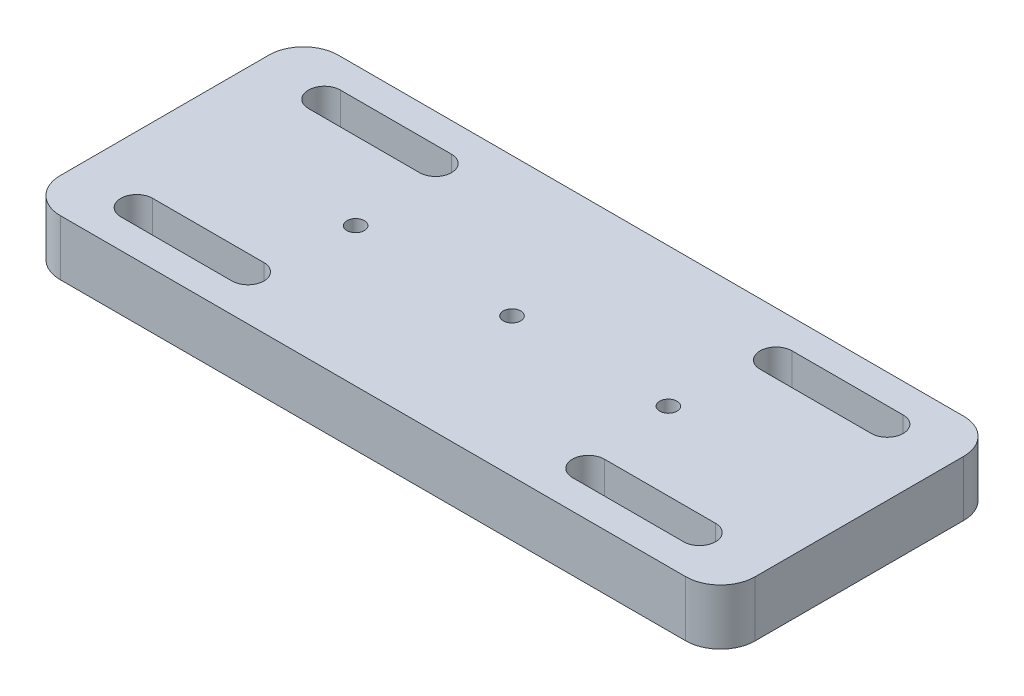
SolidWorks part; units mm, degrees
material "6061 合金"
ref_plane "前视基准面" through (0, 0, 0) normal (0, 0, 1) x (1, 0, 0)
ref_plane "上视基准面" through (0, 0, 0) normal (0, 1, 0) x (1, 0, 0)
ref_plane "右视基准面" through (0, 0, 0) normal (1, 0, 0) x (0, 0, -1)
sketch "草图1" plane through (0, 0, 0) normal (0, 1, 0) x (1, 0, 0)
  line L0 (-40.5, 13.5) -> (-24.5, 13.5) construction
  line L1 (-50, -20) -> (50, -20)
  line L2 (-50, -20) -> (-50, 20)
  line L3 (-50, 20) -> (50, 20)
  line L4 (50, -20) -> (50, 20)
  line L5 (0, 20) -> (0, -20) construction
  line L6 (-50, 0) -> (50, 0) construction
  line L7 (-30, -4) -> (30, -4) construction
  line L8 (-30, -4) -> (-30, 4) construction
  line L9 (-30, 4) -> (30, 4) construction
  line L10 (30, -4) -> (30, 4) construction
  line L11 (0, 4) -> (0, -4) construction
  line L12 (-30, 0) -> (30, 0) construction
  line L13 (-32.5, -13.5) -> (32.5, -13.5) construction
  line L14 (-32.5, -13.5) -> (-32.5, 13.5) construction
  line L15 (-32.5, 13.5) -> (32.5, 13.5) construction
  line L16 (32.5, -13.5) -> (32.5, 13.5) construction
  line L17 (0, 13.5) -> (0, -13.5) construction
  line L18 (-32.5, 0) -> (32.5, 0) construction
  line L19 (-40.5, -13.5) -> (-24.5, -13.5) construction
  line L20 (-40.5, 15.8) -> (-24.5, 15.8)
  line L21 (-40.5, 11.2) -> (-24.5, 11.2)
  line L22 (-40.5, -11.2) -> (-24.5, -11.2)
  line L23 (-40.5, -15.8) -> (-24.5, -15.8)
  line L24 (40.5, 13.5) -> (24.5, 13.5) construction
  line L25 (40.5, 15.8) -> (24.5, 15.8)
  line L26 (40.5, 11.2) -> (24.5, 11.2)
  line L27 (40.5, -13.5) -> (24.5, -13.5) construction
  line L28 (40.5, -11.2) -> (24.5, -11.2)
  line L29 (40.5, -15.8) -> (24.5, -15.8)
  arc A0 (-40.5, 15.8) -> (-40.5, 11.2) centre (-40.5, 13.5) ccw
  arc A1 (-24.5, 11.2) -> (-24.5, 15.8) centre (-24.5, 13.5) ccw
  arc A2 (-40.5, -11.2) -> (-40.5, -15.8) centre (-40.5, -13.5) ccw
  arc A3 (-24.5, -15.8) -> (-24.5, -11.2) centre (-24.5, -13.5) ccw
  arc A4 (40.5, 15.8) -> (40.5, 11.2) centre (40.5, 13.5) cw
  arc A5 (24.5, 11.2) -> (24.5, 15.8) centre (24.5, 13.5) cw
  arc A6 (40.5, -11.2) -> (40.5, -15.8) centre (40.5, -13.5) cw
  arc A7 (24.5, -15.8) -> (24.5, -11.2) centre (24.5, -13.5) cw
  point P0 (0, 0)
  point P4 (0, 0)
  point P11 (0, 0)
  point P25 (-32.5, 13.5)
  point P33 (-32.5, -13.5)
  point P39 (32.5, 13.5)
  point P46 (32.5, -13.5)
  dimension "D5" = 27
  dimension "D7" = 2.3
  dimension "D1" = 40
  dimension "D2" = 100
  dimension "D3" = 8
  dimension "D4" = 60
  dimension "D6" = 65
  dimension "D8" = 16
extrude "凸台-拉伸1" add sketch "草图1" along normal blind 8
sketch "草图2" plane through (0, 8, 0) normal (0, 1, 0) x (1, 0, 0)
  line L1 (-30, -4) -> (30, -4) construction
  line L2 (-30, -4) -> (-30, 4) construction
  line L3 (-30, 4) -> (30, 4) construction
  line L4 (30, -4) -> (30, 4) construction
  line L5 (0, 4) -> (0, -4) construction
  line L6 (-30, 0) -> (30, 0) construction
  circle A0 centre (0, 0) radius 1.5
  circle A1 centre (22.5, 0) radius 1.5
  circle A2 centre (-22.5, 0) radius 1.5
  point P0 (0, 0)
  dimension "D3" = 3
  dimension "D4" = 3
  dimension "D5" = 3
  dimension "D6" = 45
  dimension "D7" = 22.5
  dimension "D1" = 8
  dimension "D2" = 60
hole_wizard "M3 螺纹孔2" positions "3D草图2" profile "草图3" tap size "M3" standard "GB"
sketch3d "3D草图2"
  line L0 (0, 8, -4) -> (0, 8, 4) construction
  line L1 (-30, 8, 0) -> (30, 8, 0) construction
  point P0 (-22.5, 8, 0)
  point P3 (0, 0, 0)
  point P6 (22.5, 8, 0)
  point P9 (0, 0, 0)
  point P12 (0, 0, 0)
  point P14 (0, 8, 0)
  point P19 (0, 8, 0)
  point P23 (0, 8, 0)
  point P25 (0, 8, 0)
  point P27 (0, 8, 0)
  point P29 (0, 8, 0)
  point P36 (0, 8, 0)
sketch "草图3" plane through (-22.5, 8, 0) normal (1, 0, 0) x (0, 0, 1)
  line L0 (0, 0) -> (0, 22.2511)
  line L1 (0, 22.2511) -> (1.25, 21.5)
  line L2 (1.25, 21.5) -> (1.25, 0)
  line L5 (1.25, 0) -> (0, 0)
  line L10 (0, 22.2511) -> (-1.25, 21.5) construction
  line L11 (0, -6.35) -> (0, 107.95) construction
  dimension "螺纹孔钻头直径" = 2.5
  dimension "螺纹孔钻头深度" = 21.5
  dimension "导头角度" = 118
cosmetic thread "孔螺蚊线2" parameters "D1"=8, "D2"=3
cosmetic thread "孔螺蚊线10" parameters "D1"=8, "D2"=3
cosmetic thread "孔螺蚊线11" parameters "D1"=8, "D2"=3
cosmetic thread "孔螺蚊线12" parameters "D1"=8, "D2"=3
cosmetic thread "孔螺蚊线13" parameters "D1"=8, "D2"=3
cosmetic thread "孔螺蚊线14" parameters "D1"=8, "D2"=3
cosmetic thread "孔螺蚊线15" parameters "D1"=8, "D2"=3
cosmetic thread "孔螺蚊线16" parameters "D1"=8, "D2"=3
cosmetic thread "孔螺蚊线17" parameters "D1"=8, "D2"=3
cosmetic thread "孔螺蚊线18" parameters "D1"=8, "D2"=3
cosmetic thread "孔螺蚊线19" parameters "D1"=8, "D2"=3
cosmetic thread "孔螺蚊线20" parameters "D1"=8, "D2"=3
fillet "圆角1" radius 5 4 edges at (50, 4, 20) (-50, 4, -20) (50, 4, -20) (-50, 4, 20)
sketch "草图4" plane through (0, 0, 0) normal (0, -1, 0) x (1, 0, 0)
  circle A0 centre (-22.5, 0) radius 3
  circle A1 centre (0, 0) radius 3
  circle A2 centre (22.5, 0) radius 3
  dimension "D1" = 6
  dimension "D2" = 6
  dimension "D3" = 6
